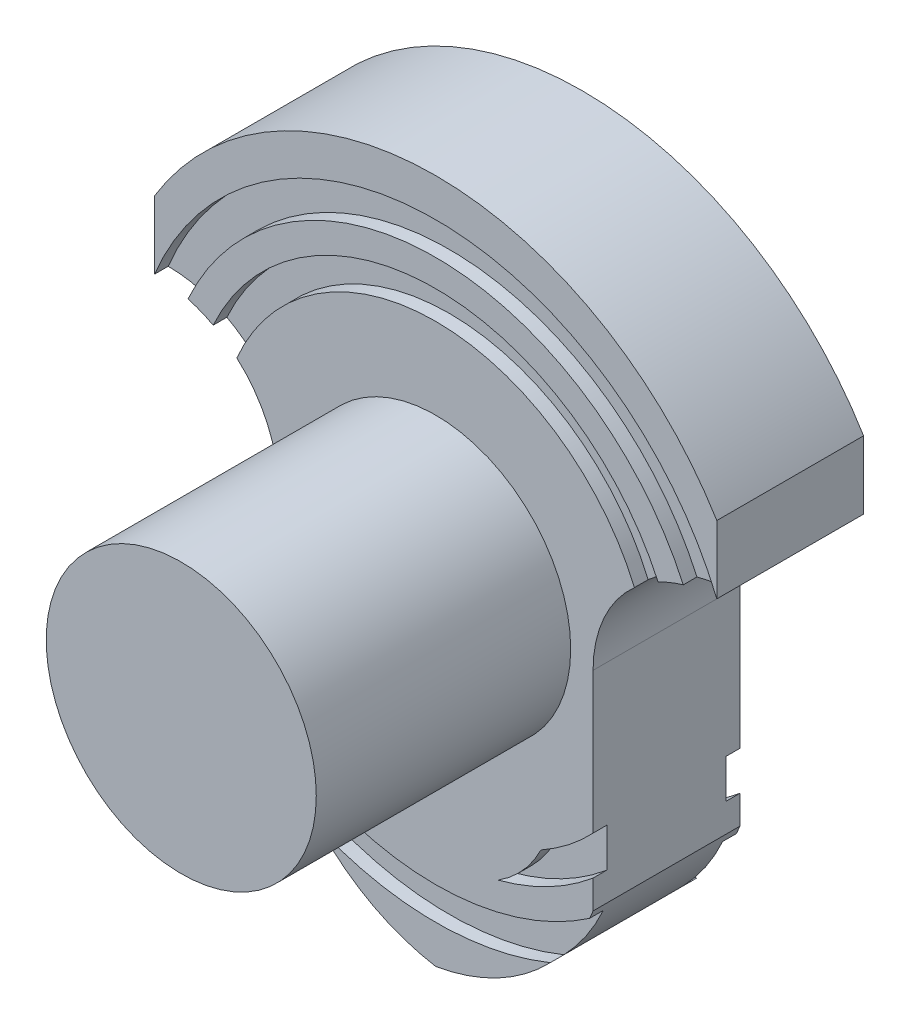
SolidWorks part; units mm, degrees
ref_plane "Front Plane" through (0, 0, 0) normal (0, 0, 1) x (1, 0, 0)
ref_plane "Top Plane" through (0, 0, 0) normal (0, 1, 0) x (1, 0, 0)
ref_plane "Right Plane" through (0, 0, 0) normal (1, 0, 0) x (0, 0, -1)
other "Center of Mass"
sketch "Sketch2" plane through (0, 0, 0) normal (0, 0, 1) x (1, 0, 0)
  line L0 (0, -88.9) -> (0, 9.2407) construction
  line L1 (20.4293, -72.4469) -> (20.4293, -45.3998)
  line L2 (36.4911, -29.3381) -> (36.4911, -20.5324)
  line L4 (-20.4293, -72.4469) -> (-20.4293, -45.3998)
  line L5 (-36.4911, -29.3381) -> (-36.4911, -20.5324)
  arc A0 (0, -88.9) -> (-20.4293, -72.4469) centre (4.4826, -62.4244) cw
  arc A1 (-20.4293, -45.3998) -> (-36.4911, -29.3381) centre (-36.4911, -45.3998) ccw
  arc A2 (-36.4911, -20.5324) -> (0, 0) centre (0, -42.6929) cw
  arc A6 (0, -88.9) -> (20.4293, -72.4469) centre (-4.4826, -62.4244) ccw
  arc A7 (20.4293, -45.3998) -> (36.4911, -29.3381) centre (36.4911, -45.3998) cw
  arc A8 (36.4911, -20.5324) -> (0, 0) centre (0, -42.6929) ccw
  circle A9 centre (0, -62.23) radius 15.24
  dimension "D5" = 26.8524
  dimension "D7" = 42.6929
  dimension "D2" = 30.48
  dimension "D3" = 62.23
  dimension "D4" = 26.8524
  dimension "D6" = 42.6929
  dimension "D1" = 88.9
extrude "Boss-Extrude2" add sketch "Sketch2" along normal blind 19.05
sketch "Sketch3" plane through (0, 0, 19.05) normal (0, 0, 1) x (1, 0, 0)
  line L0 (0, 0) -> (0, -44.45) construction
  circle A0 centre (0, -44.45) radius 39.4964
  circle A1 centre (0, -44.45) radius 35.26
  dimension "D1" = 44.45
extrude "Cut-Extrude2" cut sketch "Sketch3" against normal blind 1.778
sketch "Sketch4" plane through (0, 0, 19.05) normal (0, 0, 1) x (1, 0, 0)
  line L0 (0, 0) -> (0, -44.45) construction
  circle A0 centre (0, -44.45) radius 28.069
  circle A1 centre (0, -44.45) radius 31.7462
extrude "Cut-Extrude3" cut sketch "Sketch4" against normal blind 1.778
sketch "Sketch5" plane through (0, 0, 0) normal (0, 0, -1) x (-1, 0, 0)
  circle A1 centre (0, -44.45) radius 35.26
  circle A2 centre (0, -44.45) radius 35.26
  circle A3 centre (0, -44.45) radius 39.4964
  circle A4 centre (0, -44.45) radius 39.4964
  dimension "D1" = 0
  dimension "D2" = 0
extrude "Cut-Extrude4" cut sketch "Sketch5" against normal blind 1.778
sketch "Sketch7" plane through (0, 0, 0) normal (0, 0, -1) x (-1, 0, 0)
  circle A1 centre (0, -44.45) radius 31.7462
  circle A2 centre (0, -44.45) radius 31.7462
  circle A3 centre (0, -44.45) radius 28.069
  circle A4 centre (0, -44.45) radius 28.069
  dimension "D1" = 0
  dimension "D2" = 0
extrude "Cut-Extrude5" cut sketch "Sketch7" against normal blind 1.778
sketch "Sketch9" plane through (0, 0, 19.05) normal (0, 0, 1) x (1, 0, 0)
  circle A0 centre (0, -62.23) radius 15.24
extrude "Boss-Extrude3" add sketch "Sketch9" against normal blind 6.35
sketch "Sketch10" plane through (0, 0, 19.05) normal (0, 0, 1) x (1, 0, 0)
  line L0 (0, 0) -> (0, -44.45) construction
  circle A0 centre (0, -44.45) radius 17.526
  dimension "D2" = 35.052
  dimension "D1" = 44.45
extrude "Boss-Extrude4" add sketch "Sketch10" along normal blind 33.02
other "Center of Mass Reference Point1"
